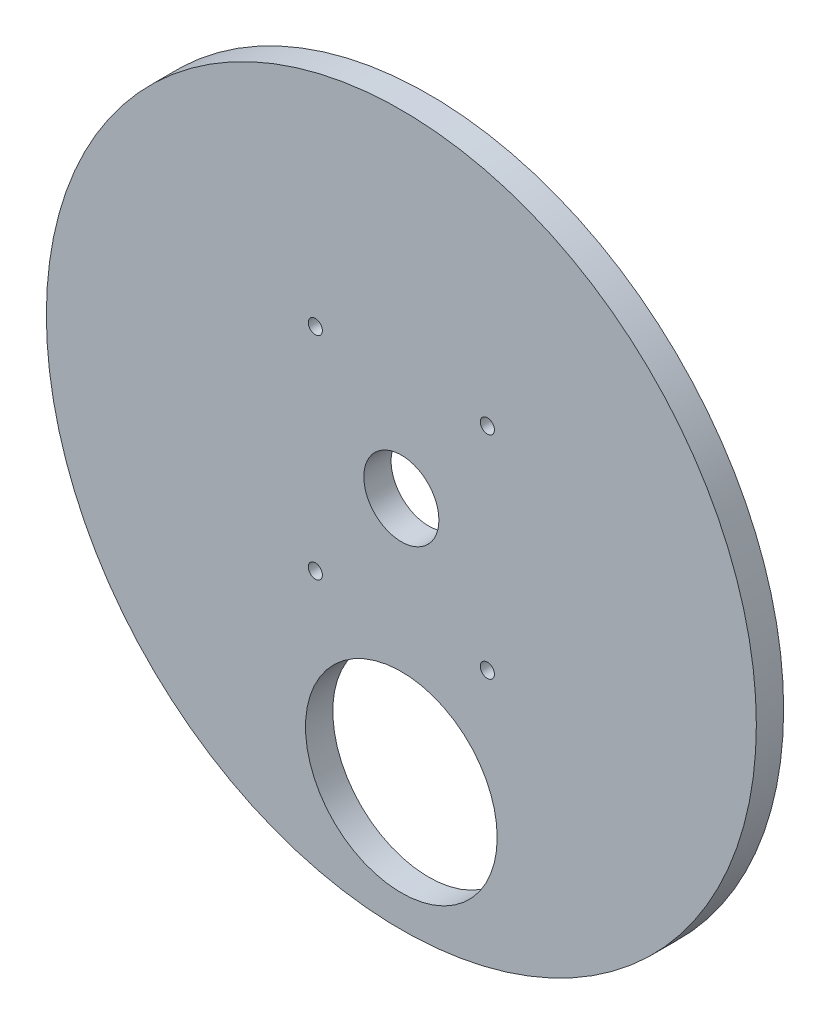
SolidWorks part; units mm, degrees
ref_plane "Front Plane" through (0, 0, 0) normal (0, 0, 1) x (1, 0, 0)
ref_plane "Top Plane" through (0, 0, 0) normal (0, 1, 0) x (1, 0, 0)
ref_plane "Right Plane" through (0, 0, 0) normal (1, 0, 0) x (0, 0, -1)
sketch "Sketch1" plane through (0, 0, 0) normal (0, 0, 1) x (1, 0, 0)
  line L0 (0, 0) -> (0, -50000) construction
  circle A0 centre (0, -46.743) radius 127
  circle A1 centre (0, -8.643) radius 165.1
  circle A3 centre (0, -114.3) radius 44.577
  circle A7 centre (0, 0) radius 17.4625
  point P4 (0, -173.743)
  point P16 (0, 0)
  point P76 (0, 0)
  dimension "D1" = 114.3
  dimension "D4" = 89.154
  dimension "D5" = 67.557
  dimension "D6" = 330.2
  dimension "D2" = 34.925
  dimension "D3" = 254
extrude "Boss-Extrude1" add sketch "Sketch1" along normal blind 12.7 contours A1 L0 A0 | A0 L0 A7 A3 | L0 A0 A3 A7 | L0 A1 A0
sketch "Sketch9" plane through (0, 0, 0) normal (0, 0, 1) x (1, 0, 0)
  line L1 (-40.005, 49.2125) -> (40.005, 49.2125)
  line L2 (-40.005, 49.2125) -> (-40.005, -147.6375)
  line L3 (-40.005, -147.6375) -> (40.005, -147.6375)
  line L4 (40.005, 49.2125) -> (40.005, -147.6375)
  circle A3 centre (-40.005, -49.2125) radius 3.175
  circle A4 centre (-40.005, 49.2125) radius 3.175
  circle A5 centre (40.005, 49.2125) radius 3.175
  circle A6 centre (40.005, -49.2125) radius 3.175
  point P4 (0, 49.2125)
  dimension "D1" = 49.2125
  dimension "D2" = 40.005
  dimension "D5" = 98.425
  dimension "D6" = 6.35
  dimension "D3" = 196.85
hole_wizard "CBORE for 1/4 Hex Head Bolt1" positions "Sketch11" profile "Sketch10" counterbore size "1/4" standard "ANSI Inch"
sketch "Sketch11" plane through (0, 0, 0) normal (0, 0, -1) x (-1, 0, 0)
  point P0 (-40.005, 49.2125)
  point P3 (40.005, 49.2125)
  point P6 (40.005, -49.2125)
  point P9 (-40.005, -49.2125)
  dimension "D1" = 98.425
  dimension "D2" = 40.005
sketch "Sketch10" plane through (40.005, 49.2125, 0) normal (1, 0, 0) x (0, 1, 0)
  line L0 (0, 0) -> (0, 14.6754)
  line L1 (0, 14.6754) -> (3.2893, 12.699)
  line L2 (3.2893, 12.699) -> (3.2893, 3.81)
  line L3 (3.2893, 3.81) -> (6.35, 3.81)
  line L4 (6.35, 3.81) -> (6.35, 0)
  line L5 (6.35, 0) -> (0, 0)
  line L10 (0, 14.6754) -> (-3.2893, 12.699) construction
  line L11 (0, -6.35) -> (0, 107.95) construction
  dimension "Hole Dia." = 6.5786
  dimension "Hole Depth" = 12.699
  dimension "C'Bore Dia." = 12.7
  dimension "C'Bore Depth" = 3.81
  dimension "Drill Angle" = 118
